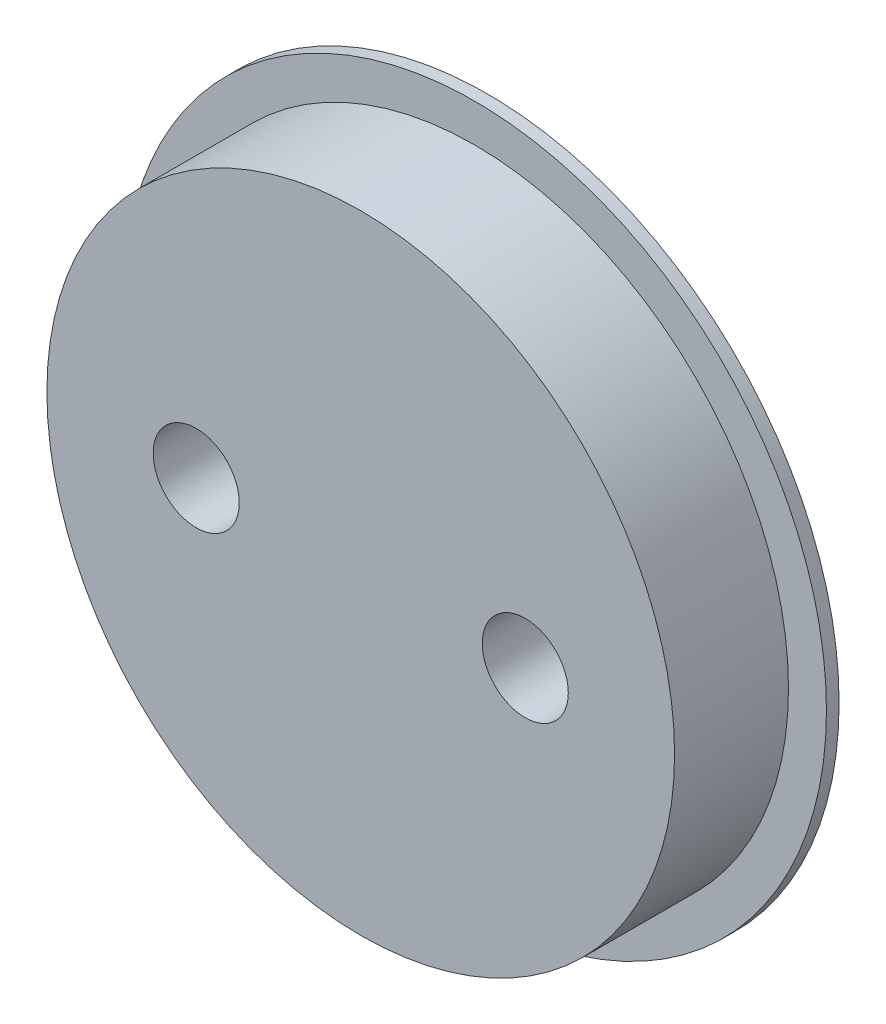
SolidWorks part; units mm, degrees
material "ABS"
ref_plane "前视基准面" through (0, 0, 0) normal (0, 0, 1) x (1, 0, 0)
ref_plane "上视基准面" through (0, 0, 0) normal (0, 1, 0) x (1, 0, 0)
ref_plane "右视基准面" through (0, 0, 0) normal (1, 0, 0) x (0, 0, -1)
sketch "草图1" plane through (0, 0, 0) normal (0, 0, 1) x (1, 0, 0)
  line L0 (6.5, 0) -> (-6.5, 0) construction
  circle A0 centre (0, 0) radius 12.4
  circle A1 centre (-6.5, 0) radius 1.7
  circle A2 centre (6.5, 0) radius 1.7
  point P6 (0, 0)
  dimension "D1" = 24.8
  dimension "D2" = 3.4
  dimension "D3" = 13
extrude "凸台-拉伸1" add sketch "草图1" along normal blind 5
sketch "草图2" plane through (0, 0, 0) normal (0, 0, 1) x (1, 0, 0)
  circle A0 centre (0, 0) radius 13.9
  circle A1 centre (0, 0) radius 12.4
  circle A2 centre (0, 0) radius 12.4
  dimension "D2" = 1.5
  dimension "D1" = 0
extrude "凸台-拉伸2" add sketch "草图2" along normal blind 0.5
